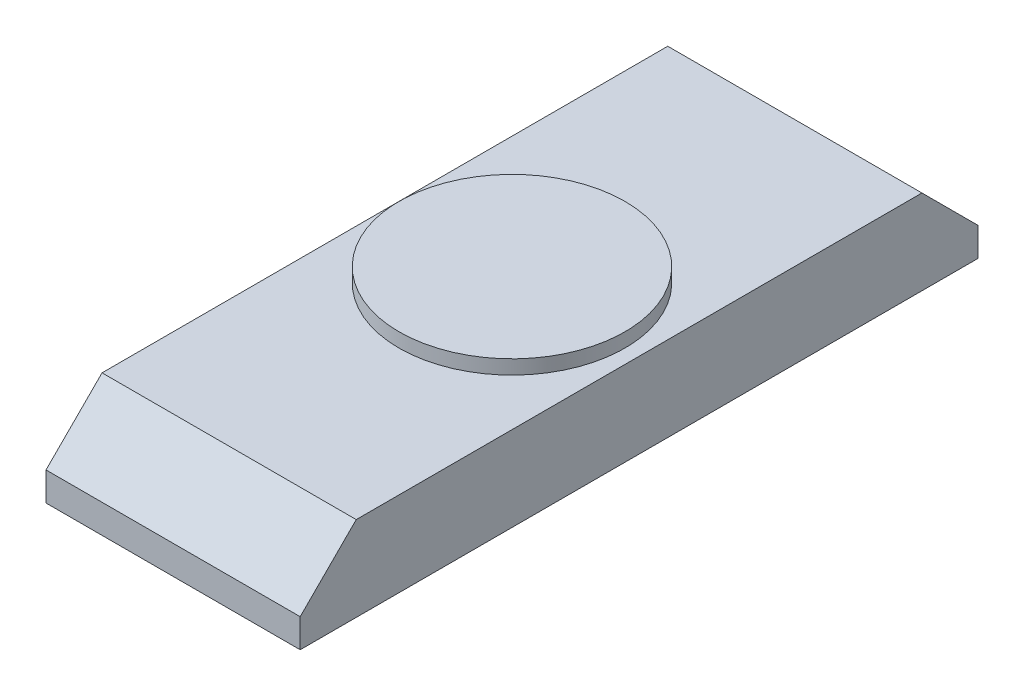
SolidWorks part; units mm, degrees
material "Pine"
ref_plane "Front Plane" through (0, 0, 0) normal (0, 0, 1) x (1, 0, 0)
ref_plane "Top Plane" through (0, 0, 0) normal (0, 1, 0) x (1, 0, 0)
ref_plane "Right Plane" through (0, 0, 0) normal (1, 0, 0) x (0, 0, -1)
sketch "Sketch2" plane through (0, 0, 0) normal (0, 1, 0) x (1, 0, 0)
  line L1 (0, 0) -> (57.15, 0)
  line L2 (0, 0) -> (0, -152.4)
  line L3 (0, -152.4) -> (57.15, -152.4)
  line L4 (57.15, 0) -> (57.15, -152.4)
  dimension "D1" = 57.15
  dimension "D2" = 152.4
extrude "Boss-Extrude1" add sketch "Sketch2" along normal blind 19.05
sketch "Sketch3" plane through (57.15, 0, 0) normal (1, 0, 0) x (0, 0, -1)
  line L1 (-152.4, 19.05) -> (-152.4, 0) construction
  line L3 (0, 19.05) -> (0, 0) construction
  line L4 (-152.4, 6.4472) -> (-139.7972, 19.05)
  line L5 (-152.4, 19.05) -> (0, 19.05) construction
  line L6 (0, 6.4472) -> (-12.6028, 19.05)
  line L7 (-12.6028, 19.05) -> (0, 19.05)
  line L8 (0, 19.05) -> (0, 6.4472)
  line L10 (-139.7972, 19.05) -> (-152.4, 19.05)
  line L11 (-152.4, 19.05) -> (-152.4, 6.4472)
extrude "Cut-Extrude2" cut sketch "Sketch3" against normal blind 57.15
sketch "Sketch5" plane through (0, 19.05, 0) normal (0, 1, 0) x (1, 0, 0)
  line L1 (57.15, -139.7972) -> (0, -139.7972)
  circle A0 centre (28.575, -76.2) radius 25.4
  dimension "D1" = 50.8
extrude "Boss-Extrude2" add sketch "Sketch5" along normal blind 3.175 contours A0
